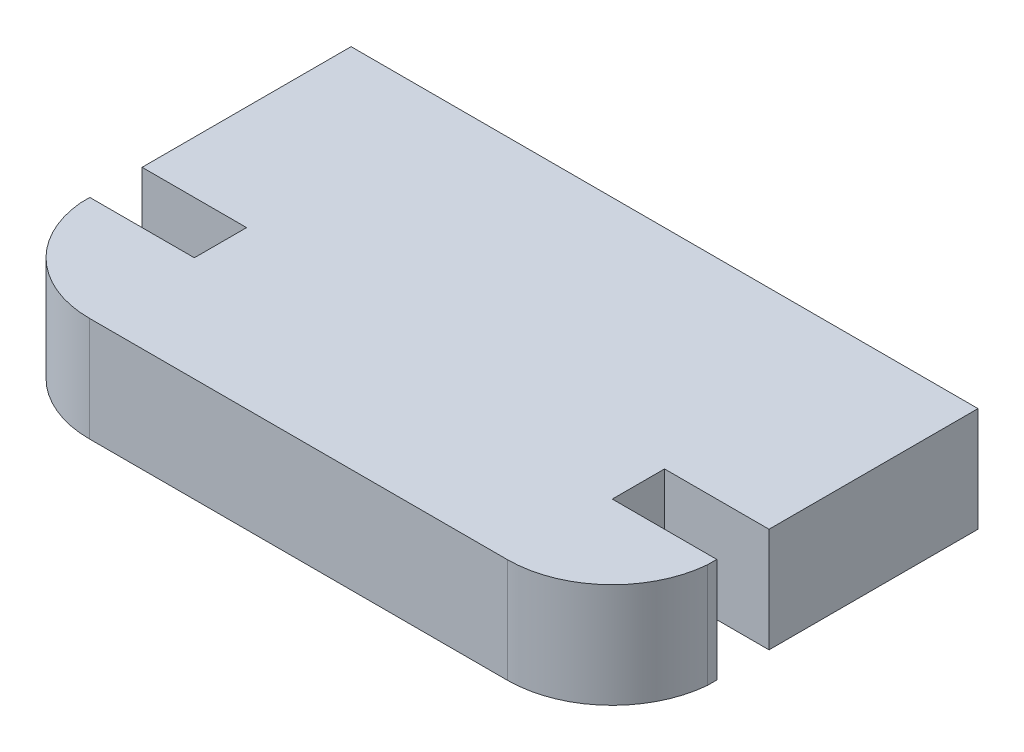
SolidWorks part; units mm, degrees
ref_plane "Front Plane" through (0, 0, 0) normal (0, 0, 1) x (1, 0, 0)
ref_plane "Top Plane" through (0, 0, 0) normal (0, 1, 0) x (1, 0, 0)
ref_plane "Right Plane" through (0, 0, 0) normal (1, 0, 0) x (0, 0, -1)
sketch "Sketch1" plane through (0, 0, 0) normal (0, 1, 0) x (1, 0, 0)
  line L1 (-9.525, 5.5625) -> (9.525, 5.5625)
  line L2 (-9.525, 5.5625) -> (-9.525, -5.5625)
  line L3 (-9.525, -5.5625) -> (9.525, -5.5625)
  line L4 (9.525, 5.5625) -> (9.525, -5.5625)
  line L5 (-9.525, 5.5625) -> (9.525, -5.5625) construction
  line L6 (-9.525, -5.5625) -> (9.525, 5.5625) construction
  point P0 (0, 0)
  dimension "D1" = 19.05
  dimension "D2" = 11.125
extrude "Boss-Extrude1" add sketch "Sketch1" along normal blind 3.175
ref_plane "Plane1" through (0, 3.175, 0) normal (0, 1, 0) x (1, 0, 0)
sketch "Sketch2" plane through (0, 3.175, 0) normal (0, 1, 0) x (1, 0, 0)
  line L0 (-9.525, 5.5625) -> (-9.525, -0.7875)
  line L1 (-9.525, 5.5625) -> (-9.525, -5.5625) construction
  line L2 (0, 5.5625) -> (0, -4.4259) construction
  line L3 (9.525, 5.5625) -> (-9.525, 5.5625) construction
  line L4 (9.525, 5.5625) -> (9.525, -0.7875)
  line L5 (-9.525, -0.7875) -> (-6.35, -0.7875)
  line L6 (-6.35, -0.7875) -> (-6.35, -2.375)
  line L7 (-6.35, -2.375) -> (-9.525, -2.375)
  line L8 (9.525, -0.7875) -> (6.35, -0.7875)
  line L9 (6.35, -2.375) -> (9.525, -2.375)
  line L10 (6.35, -0.7875) -> (6.35, -2.375)
  line L11 (-9.525, 5.5625) -> (9.525, 5.5625)
  line L15 (9.525, -0.7875) -> (9.525, -2.375)
  line L16 (9.525, -2.375) -> (9.525, -5.5625)
  line L17 (-9.525, -5.5625) -> (9.525, -5.5625) construction
  line L18 (-9.525, -2.657) -> (-9.525, -2.375)
  line L19 (-9.525, -5.5625) -> (-9.525, -2.375)
  line L20 (-9.525, -0.7875) -> (-9.525, -2.375)
  line L21 (-6.35, -5.5625) -> (6.35, -5.5625)
  line L22 (9.525, -2.657) -> (9.525, -2.375)
  line L23 (-9.525, -5.5625) -> (-6.35, -5.5625)
  line L24 (6.35, -5.5625) -> (9.525, -5.5625)
  arc A2 (-6.35, -5.5625) -> (-9.525, -2.657) centre (-6.35, -2.375) cw
  arc A3 (6.35, -5.5625) -> (9.525, -2.657) centre (6.35, -2.375) ccw
  point P28 (0, -5.5625)
  dimension "D1" = 6.35
  dimension "D2" = 3.175
  dimension "D3" = 1.5875
extrude "Cut-Extrude2" cut sketch "Sketch2" against normal blind 3.175 contours L5 L20 L7 L6 | L23 A2 L19 | A3 L24 L16 | L15 L8 L10 L9
